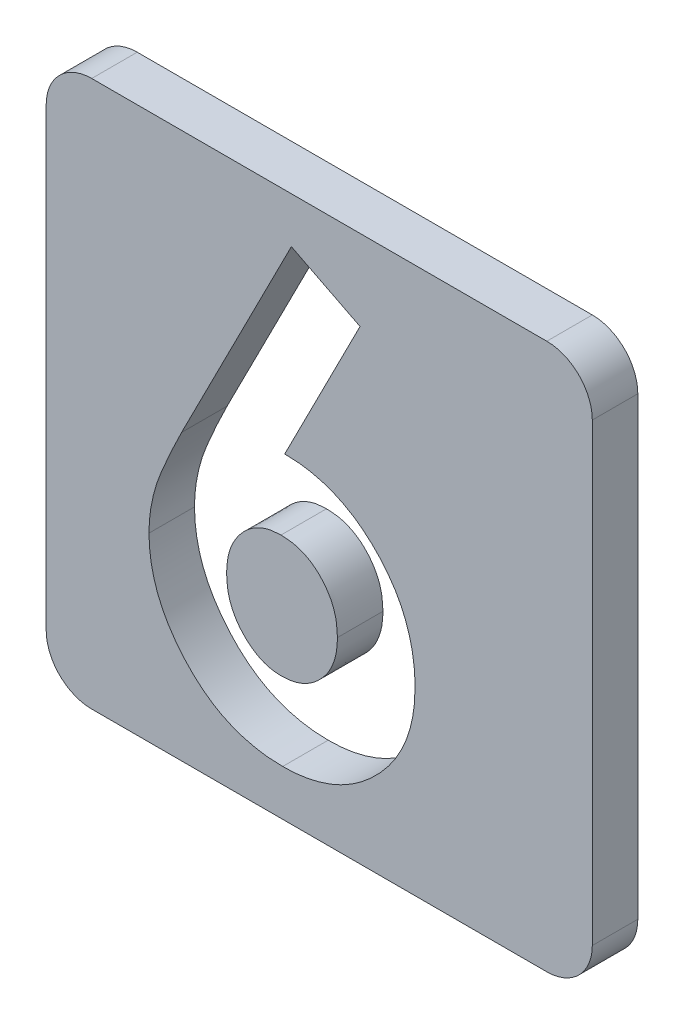
SolidWorks part; units mm, degrees
ref_plane "Front Plane" through (0, 0, 0) normal (0, 0, 1) x (1, 0, 0)
ref_plane "Top Plane" through (0, 0, 0) normal (0, 1, 0) x (1, 0, 0)
ref_plane "Right Plane" through (0, 0, 0) normal (1, 0, 0) x (0, 0, -1)
sketch "Sketch1" plane through (0, 0, 0) normal (0, 0, 1) x (1, 0, 0)
  line L1 (-50, 60) -> (50, 60)
  line L2 (-60, 50) -> (-60, -50)
  line L3 (-50, -60) -> (50, -60)
  line L4 (60, 50) -> (60, -50)
  line L5 (-60, 60) -> (60, -60) construction
  line L6 (-60, -60) -> (60, 60) construction
  arc A0 (-60, -50) -> (-50, -60) centre (-50, -50) ccw
  arc A1 (50, -60) -> (60, -50) centre (50, -50) ccw
  arc A2 (50, 60) -> (60, 50) centre (50, 50) cw
  arc A3 (-50, 60) -> (-60, 50) centre (-50, 50) ccw
  point P0 (0, 0)
  dimension "D3" = 10
  dimension "D1" = 120
  dimension "D2" = 120
extrude "Boss-Extrude1" add sketch "Sketch1" along normal blind 10 contours A3 L2 A0 L3 A1 L4 A2 L1
sketch "Sketch2" plane through (0, 0, 10) normal (0, 0, 1) x (1, 0, 0)
  line L0 (0, 0) -> (0, 40) construction
  line L1 (-50, 50) -> (50, 50) construction
  line L2 (-50, 50) -> (-50, -50) construction
  line L3 (-50, -50) -> (50, -50) construction
  line L4 (50, 50) -> (50, -50) construction
  line L5 (-50, 50) -> (50, -50) construction
  line L6 (-50, -50) -> (50, 50) construction
  line L7 (0, 40) -> (-40, 40) construction
  line L8 (-40, 40) -> (-40, 0) construction
  line L9 (-40, 0) -> (0, 0) construction
  line L11 (0, 20) -> (-20, 20) construction
  line L12 (-20, 40) -> (-20, 20) construction
  circle A0 centre (0, 40) radius 4 construction
  circle A1 centre (0, 20) radius 4 construction
  circle A2 centre (0, 0) radius 4 construction
  circle A3 centre (-20, 20) radius 4 construction
  circle A4 centre (-20, 40) radius 4 construction
  circle A5 centre (-40, 40) radius 4 construction
  circle A6 centre (0, 0) radius 4 construction
  circle A7 centre (20, 0) radius 4 construction
  circle A8 centre (40, 0) radius 4 construction
  circle A9 centre (40, 20) radius 4 construction
  circle A10 centre (40, 40) radius 4 construction
  circle A11 centre (20, 20) radius 4 construction
  circle A12 centre (0, 0) radius 4 construction
  circle A13 centre (0, -20) radius 4 construction
  circle A14 centre (0, -40) radius 4 construction
  circle A15 centre (20, -40) radius 4 construction
  circle A16 centre (40, -40) radius 4 construction
  circle A17 centre (20, -20) radius 4 construction
  circle A18 centre (0, 0) radius 4 construction
  circle A19 centre (-20, 0) radius 4 construction
  circle A20 centre (-40, 0) radius 4 construction
  circle A21 centre (-40, -20) radius 4 construction
  circle A22 centre (-40, -40) radius 4 construction
  circle A23 centre (-20, -20) radius 4 construction
  text T0 "6" font "Century Gothic" height 95
  point P0 (0, 0)
  point P55 (0, 0)
  dimension "D4" = 8
  dimension "D1" = 100
  dimension "D2" = 100
  dimension "D3" = 40
  dimension "D5" = 4
extrude "Cut-Extrude4" cut sketch "Sketch2" against normal blind 10
